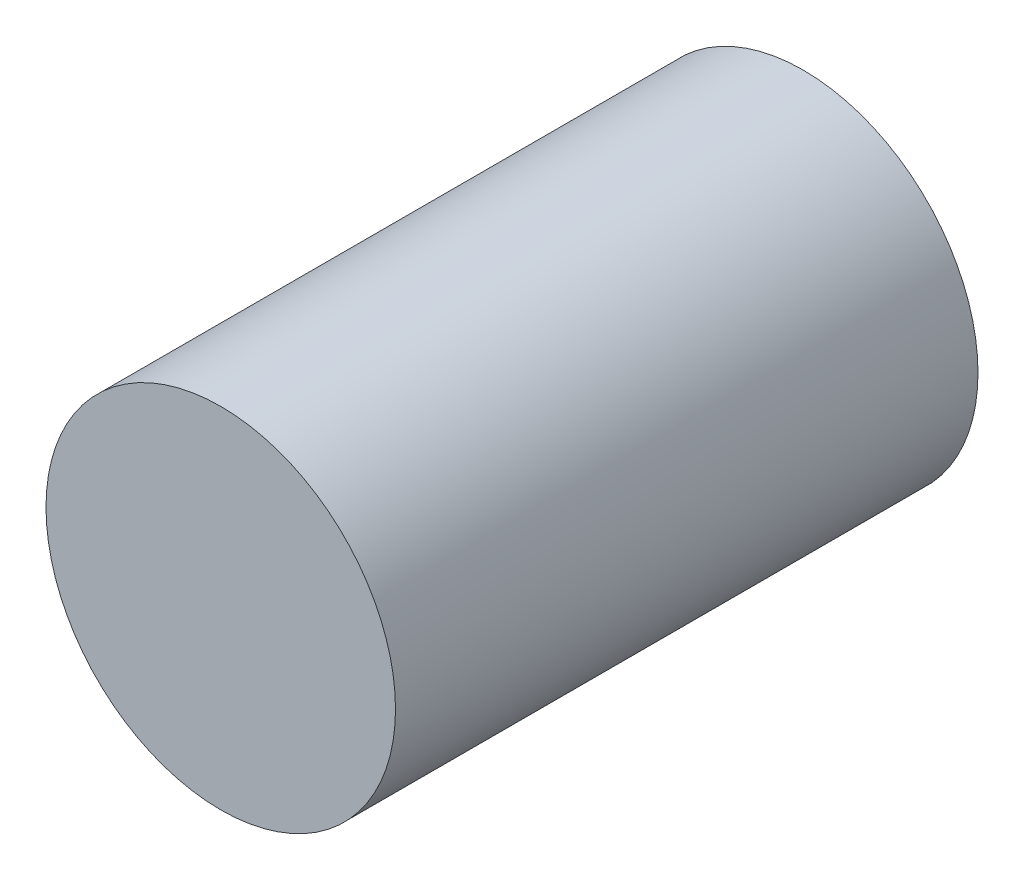
SolidWorks part; units mm, degrees
ref_plane "Front Plane" through (0, 0, 0) normal (0, 0, 1) x (1, 0, 0)
ref_plane "Top Plane" through (0, 0, 0) normal (0, 1, 0) x (1, 0, 0)
ref_plane "Right Plane" through (0, 0, 0) normal (1, 0, 0) x (0, 0, -1)
sketch "Sketch1" plane through (0, 0, 0) normal (0, 0, 1) x (1, 0, 0)
  circle A0 centre (0, 0) radius 1.5
extrude "Boss-Extrude1" add sketch "Sketch1" along normal blind 5
